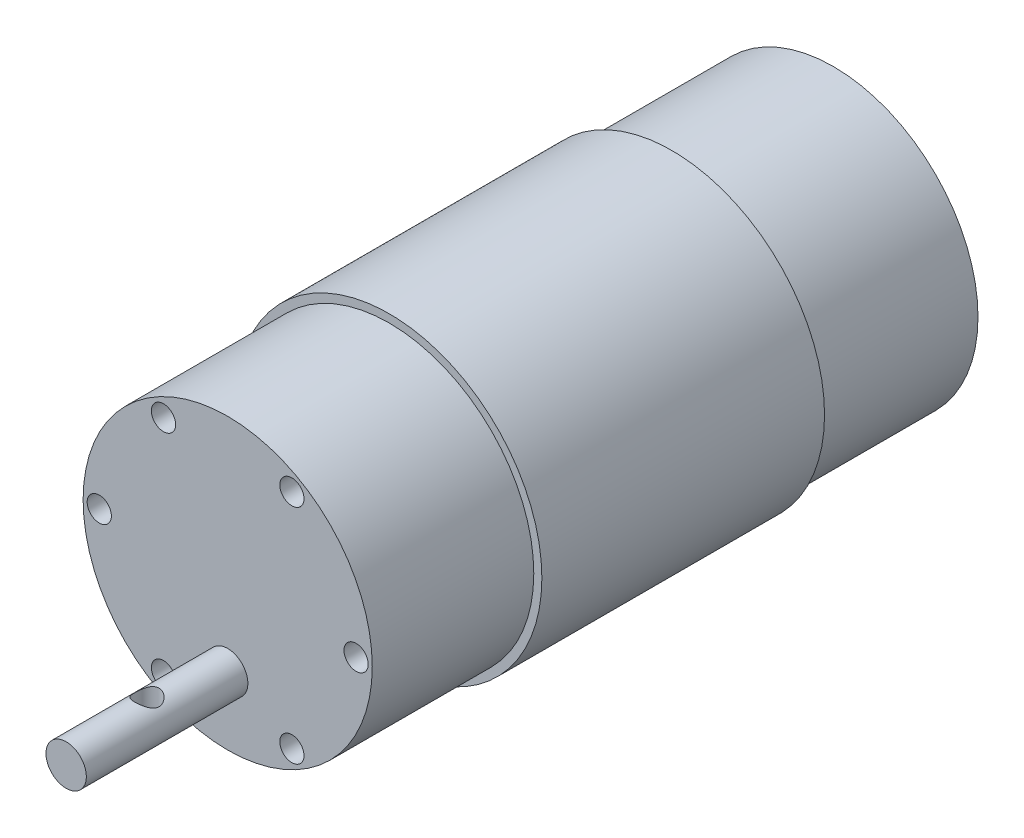
SolidWorks part; units mm, degrees
ref_plane "Front Plane" through (0, 0, 0) normal (0, 0, 1) x (1, 0, 0)
ref_plane "Top Plane" through (0, 0, 0) normal (0, 1, 0) x (1, 0, 0)
ref_plane "Right Plane" through (0, 0, 0) normal (1, 0, 0) x (0, 0, -1)
sketch "Sketch1" plane through (0, 0, 0) normal (0, 0, 1) x (1, 0, 0)
  circle A0 centre (0, 0) radius 18.9
  dimension "D1" = 37.8
extrude "Boss-Extrude1" add sketch "Sketch1" along normal blind 75
sketch "Sketch2" plane through (0, 0, 75) normal (0, 0, 1) x (1, 0, 0)
  circle A0 centre (15.9, 0) radius 1.5
  circle A1 centre (7.95, -13.7698) radius 1.5
  circle A2 centre (-7.95, -13.7698) radius 1.5
  circle A3 centre (-15.9, 0) radius 1.5
  circle A4 centre (-7.95, 13.7698) radius 1.5
  circle A5 centre (7.95, 13.7698) radius 1.5
  dimension "D1" = 3
  dimension "D2" = 15.9
  dimension "D3" = 6
extrude "Cut-Extrude1" cut sketch "Sketch2" against normal blind 8
sketch "Sketch3" plane through (0, 0, 75) normal (0, 0, 1) x (1, 0, 0)
  circle A0 centre (0, -9.5) radius 2.5
  dimension "D2" = 5
  dimension "D1" = 9.5
extrude "Boss-Extrude2" add sketch "Sketch3" along normal blind 20
sketch "Sketch5" plane through (0, 0, 75) normal (0, 0, 1) x (1, 0, 0)
  circle A0 centre (0, 0) radius 17.9
  circle A1 centre (0, 0) radius 18.9 construction
  circle A2 centre (0, 0) radius 18.9
  dimension "D1" = 1
extrude "Cut-Extrude4" cut sketch "Sketch5" against normal blind 20
sketch "Sketch6" plane through (0, 0, 0) normal (0, 0, -1) x (-1, 0, 0)
  circle A0 centre (0, 0) radius 17.9
  circle A1 centre (0, 0) radius 18.9 construction
  circle A2 centre (0, 0) radius 18.9
  dimension "D1" = 1
extrude "Cut-Extrude5" cut sketch "Sketch6" against normal blind 20
sketch "Sketch7" plane through (0, 0, 0) normal (0, 1, 0) x (1, 0, 0)
  line L0 (-2.5, -95) -> (2.5, -95) construction
  circle A0 centre (0, -85) radius 1.5
  dimension "D1" = 3
  dimension "D2" = 10
extrude "Cut-Extrude6" cut sketch "Sketch7" against normal through all
